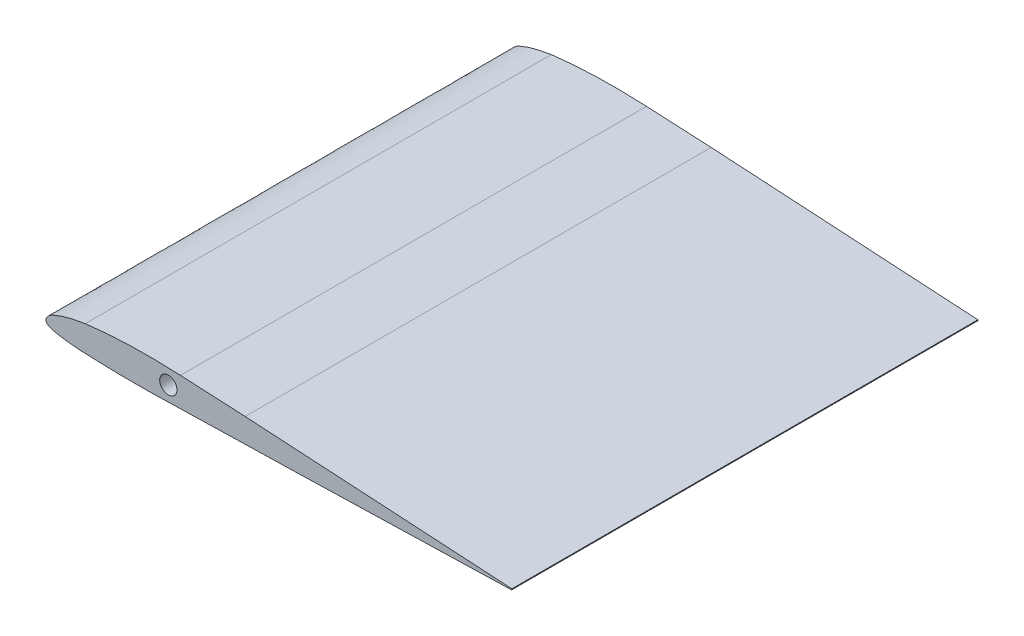
SolidWorks part; units mm, degrees
material "EPP"
ref_plane "Front Plane" through (0, 0, 0) normal (0, 0, 1) x (1, 0, 0)
ref_plane "Top Plane" through (0, 0, 0) normal (0, 1, 0) x (1, 0, 0)
ref_plane "Right Plane" through (0, 0, 0) normal (1, 0, 0) x (0, 0, -1)
sketch "Sketch3" plane through (0, 0, 0) normal (0, 0, 1) x (1, 0, 0)
  line L0 (202.9941, 8.6587) -> (110.5837, 6.1553)
  line L1 (110.5837, 6.1553) -> (45.2437, 4.5477)
  line L2 (58.6413, 17.491) -> (86.8465, 16.0766)
  line L3 (0, 35.3471) -> (0, -15.2378) construction
  line L4 (86.8465, 16.0766) -> (160.9786, 11.667)
  line L5 (160.9786, 11.667) -> (203.1607, 9.1578)
  line L6 (203.1999, 14.8061) -> (203.1999, -9.9364) construction
  line L7 (0, 0) -> (203.1999, 0) construction
  line L8 (50.8, 72.9775) -> (50.8, -63.9956) construction
  arc A0 (203.1607, 9.1578) -> (202.9941, 8.6587) centre (202.8278, 8.9915) cw
  spline S0 degree 3 poles (45.2437, 4.5477) (38.9236, 4.5689) (32.5987, 4.4374) (26.2837, 4.6938) (22.3484, 4.8536) (18.4102, 4.9373) (14.4749, 5.0971) (14.4129, 5.0996) (14.3701, 5.1734) (14.3085, 5.1801) (13.7572, 5.24) (0.0923, 5.9331) (0.0016, 8.7406) (-0.0833, 11.3694) (3.2406, 12.5979) (5.1525, 13.3198) (6.7026, 13.905) (8.2818, 14.4263) (9.8909, 14.8216) (12.2626, 15.4044) (14.6912, 15.8835) (17.1496, 16.275) knots 0 0 0 0 1 1 1 2 2 2 3 3 3 4 4 4 5 5 5 6 6 6 6.272168 6.272168 6.272168 6.272168
  spline S1 degree 3 poles (17.1496, 16.275) (28.8325, 17.7257) (42.6703, 18.2919) (58.6413, 17.491) knots 0 0 0 0 1 1 1 1
  point P17 (50.8, 17.7806)
  point P18 (50.8, 4.6844)
  dimension "D1" = 203.1999
  dimension "D2" = 50.8
extrude "Airfoil" add sketch "Sketch3" along normal blind 203.2
sketch "Sketch8" plane through (0, 0, 0) normal (0, 0, -1) x (-1, 0, 0)
  line L0 (0, 16.6795) -> (0, -1.637) construction
  line L1 (-203.1999, 12.5809) -> (-203.1999, 6.3994) construction
  line L2 (-53.34, 11.2284) -> (-53.34, 17.7099) construction
  line L3 (-53.34, 11.2284) -> (-53.34, 4.7469) construction
  line L4 (-45.2437, 4.5477) -> (-110.5837, 6.1553) construction
  circle A0 centre (-53.34, 11.2284) radius 3.7592
  arc A1 (-203.1607, 9.1578) -> (-202.9941, 8.6587) centre (-202.8278, 8.9915) ccw construction
  spline S0 degree 3 poles (-17.1496, 16.275) (-14.6912, 15.8835) (-12.2626, 15.4044) (-9.8909, 14.8216) (-8.2818, 14.4263) (-6.7026, 13.905) (-5.1525, 13.3198) (-3.2406, 12.5979) (0.0833, 11.3694) (-0.0016, 8.7406) (-0.0923, 5.9331) (-13.7572, 5.24) (-14.3085, 5.1801) (-14.3701, 5.1734) (-14.4129, 5.0996) (-14.4749, 5.0971) (-18.4102, 4.9373) (-22.3484, 4.8536) (-26.2837, 4.6938) (-32.5987, 4.4374) (-38.9236, 4.5689) (-45.2437, 4.5477) knots 0 0 0 0 0.272168 0.272168 0.272168 1.272168 1.272168 1.272168 2.272168 2.272168 2.272168 3.272168 3.272168 3.272168 4.272168 4.272168 4.272168 5.272168 5.272168 5.272168 6.272168 6.272168 6.272168 6.272168 construction
  spline S1 degree 3 poles (-58.6413, 17.491) (-42.6703, 18.2919) (-28.8325, 17.7257) (-17.1496, 16.275) knots 0 0 0 0 1 1 1 1 construction
  dimension "D1" = 7.5184
  dimension "D2" = 53.34
extrude "Camera Channel" cut sketch "Sketch8" against normal up to next
